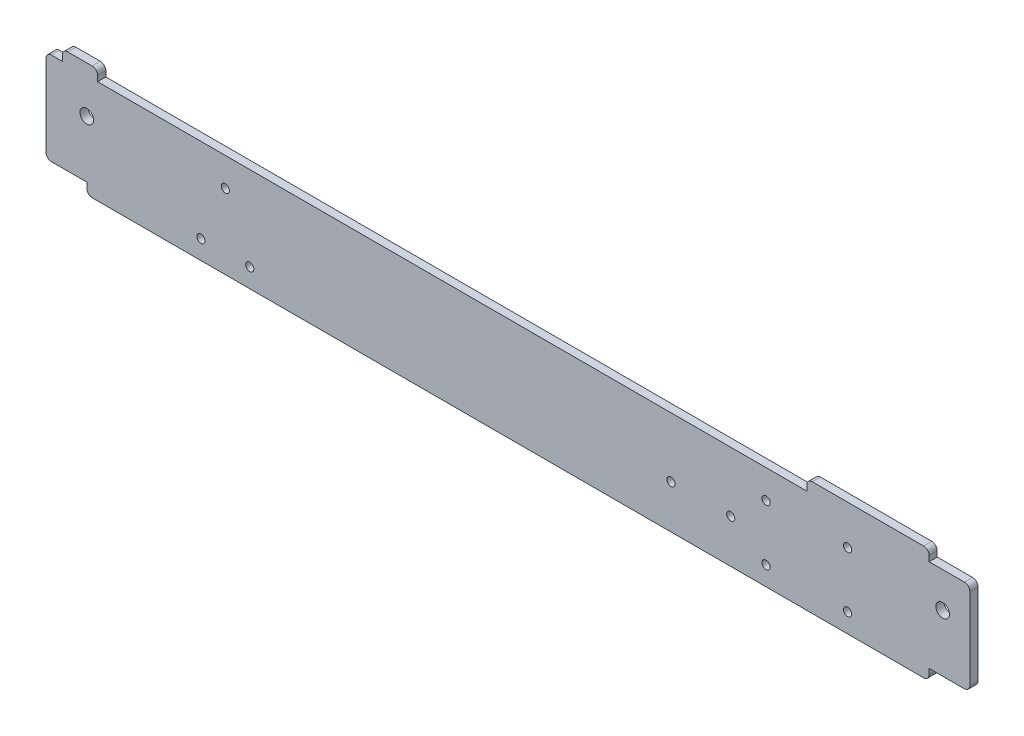
SolidWorks part; units mm, degrees
material "MDF"
ref_plane "Alzado" through (0, 0, 0) normal (0, 0, 1) x (1, 0, 0)
ref_plane "Planta" through (0, 0, 0) normal (0, 1, 0) x (1, 0, 0)
ref_plane "Vista lateral" through (0, 0, 0) normal (1, 0, 0) x (0, 0, -1)
sketch "Croquis1" plane through (0, 0, 0) normal (0, 0, 1) x (1, 0, 0)
  line L1 (-170, 21) -> (170, 21)
  line L2 (-170, 21) -> (-170, -21)
  line L3 (-170, -21) -> (170, -21)
  line L4 (170, 21) -> (170, -21)
  line L5 (-170, 21) -> (170, -21) construction
  line L6 (-170, -21) -> (170, 21) construction
  circle A0 centre (160, 4) radius 2.5
  circle A1 centre (95, 6.5) radius 1.5
  circle A3 centre (125, -14) radius 1.5
  circle A4 centre (95, -14) radius 1.5
  circle A5 centre (125, 6.5) radius 1.5
  circle A6 centre (-113, -14) radius 1.5
  circle A7 centre (-104, 6.5) radius 1.5
  circle A8 centre (-95, -14) radius 1.5
  circle A12 centre (-155, 4) radius 2.5
  circle A13 centre (82, -5) radius 1.5
  circle A14 centre (60, -5) radius 1.5
  point P0 (0, 0)
  dimension "D3" = 5
  dimension "D4" = 25
  dimension "D8" = 3
  dimension "D22" = 5
  dimension "D1" = 340
  dimension "D2" = 42
  dimension "D5" = 10
  dimension "D6" = 7
  dimension "D7" = 45
  dimension "D10" = 30
  dimension "D12" = 27.5
  dimension "D13" = 7
  dimension "D14" = 18
  dimension "D15" = 57
  dimension "D16" = 66
  dimension "D17" = 27.5
  dimension "D18" = 22
  dimension "D19" = 88
  dimension "D23" = 25
  dimension "D24" = 15
  dimension "D20" = 16
  dimension "D11" = 2
extrude "Saliente-Extruir1" add sketch "Croquis1" along normal blind 3
sketch "Croquis2" plane through (0, 0, 3) normal (0, 0, 1) x (1, 0, 0)
  line L0 (-170, -17) -> (-155, -17)
  line L1 (-170, 21) -> (-170, -21) construction
  line L2 (-155, -17) -> (-155, -21)
  line L3 (-170, -21) -> (170, -21) construction
  line L4 (-170, -17) -> (-170, -21)
  line L6 (-170, -21) -> (-155, -21)
  dimension "D1" = 15
  dimension "D2" = 4
extrude "Cortar-Extruir1" cut sketch "Croquis2" against normal through all contours L6 L2 L0 L4
mirror "Simetría1" about plane through (0, 0, 0) normal (0, 1, 0) of "Cortar-Extruir1" second plane through (0, 0, 0) second plane normal (1, 0, 0)
fillet "Redondeo1" radius 2 7 edges at (170, 17, 1.5) (155, 21, 1.5) (-170, -17, 1.5) (-155, -21, 1.5) (170, -17, 1.5) (155, -21, 1.5) (-170, 17, 1.5)
sketch "Croquis3" plane through (0, 0, 3) normal (0, 0, 1) x (1, 0, 0)
  line L0 (153, 21) -> (-155, 21) construction
  line L1 (-151, 28.8736) -> (110, 28.8736)
  line L2 (-151, 28.8736) -> (-151, 17)
  line L3 (-151, 17) -> (110, 17)
  line L4 (110, 28.8736) -> (110, 17)
  line L5 (125, -14) -> (95, 6.5) construction
  line L6 (110, -3.75) -> (110, 32.2407) construction
  dimension "D1" = 261
  dimension "D2" = 4
extrude "Cortar-Extruir2" cut sketch "Croquis3" against normal through all
sketch "Croquis7" plane through (0, 0, 3) normal (0, 0, 1) x (1, 0, 0)
  line L1 (-151, 17) -> (-164, 17)
  line L2 (-151, 17) -> (-151, 21)
  line L3 (-151, 21) -> (-164, 21)
  line L4 (-164, 17) -> (-164, 21)
  line L5 (-170, 15) -> (-170, -15) construction
  line L6 (-151, 21) -> (-155, 21) construction
  line L7 (-168, 17) -> (-155, 17) construction
  dimension "D1" = 13
  dimension "D2" = 19
extrude "Saliente-Extruir3" add sketch "Croquis7" against normal blind 3
fillet "Redondeo2" radius 2 3 edges at (-151, 21, 1.5) (-164, 21, 1.5) (110, 21, 1.5)
